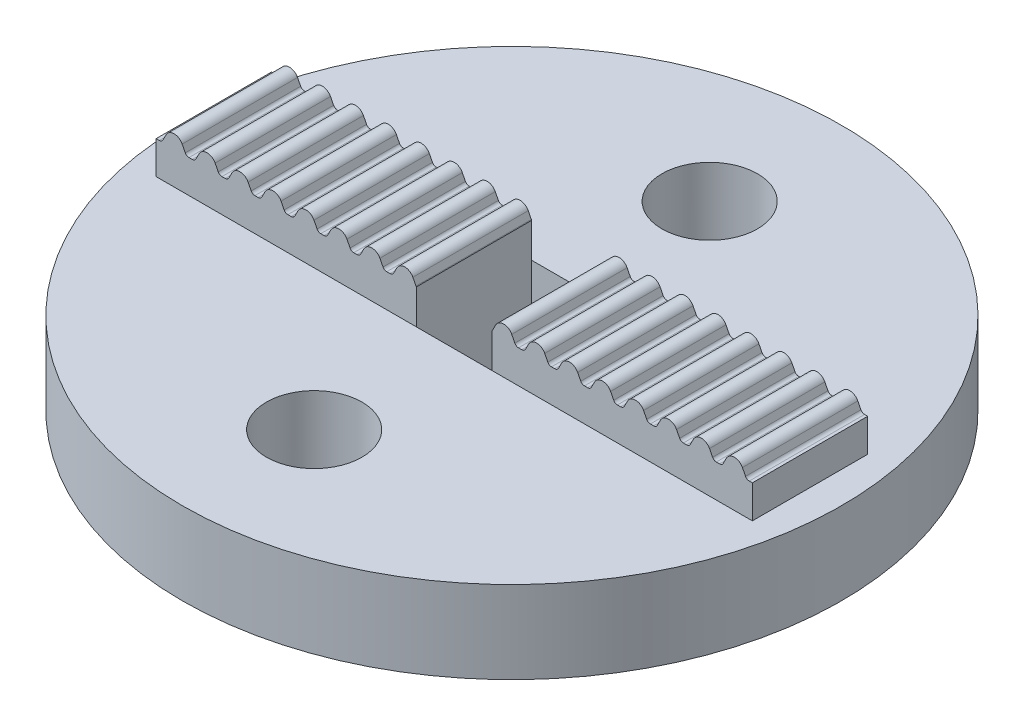
SolidWorks part; units mm, degrees
ref_plane "Front Plane" through (0, 0, 0) normal (0, 0, 1) x (1, 0, 0)
ref_plane "Top Plane" through (0, 0, 0) normal (0, 1, 0) x (1, 0, 0)
ref_plane "Right Plane" through (0, 0, 0) normal (1, 0, 0) x (0, 0, -1)
sketch "Sketch1" plane through (0, 0, 0) normal (0, 0, 1) x (1, 0, 0)
  line L0 (1.09, 0.25) -> (1.99, 0.25) construction
  line L1 (3.5789, 0.502) -> (3.7678, 0.1355)
  line L2 (3.99, 0) -> (4.18, 0)
  line L3 (1.5789, 0.502) -> (1.7678, 0.1355)
  line L4 (1.99, 0) -> (2.18, 0)
  line L5 (0.4122, 0.1355) -> (0.6011, 0.502)
  line L6 (1.09, 0.25) -> (0.19, 0.25) construction
  line L7 (0.19, 0) -> (0, 0)
  line L8 (2.4122, 0.1355) -> (2.6011, 0.502)
  line L9 (2.19, 0) -> (2, 0)
  line L10 (5.5789, 0.502) -> (5.7678, 0.1355)
  line L11 (5.99, 0) -> (6.18, 0)
  line L12 (4.4122, 0.1355) -> (4.6011, 0.502)
  line L13 (4.19, 0) -> (4, 0)
  line L14 (7.5789, 0.502) -> (7.7678, 0.1355)
  line L15 (7.99, 0) -> (8.18, 0)
  line L16 (6.4122, 0.1355) -> (6.6011, 0.502)
  line L17 (6.19, 0) -> (6, 0)
  line L18 (9.5789, 0.502) -> (9.7678, 0.1355)
  line L19 (9.99, 0) -> (10.18, 0)
  line L20 (8.4122, 0.1355) -> (8.6011, 0.502)
  line L21 (8.19, 0) -> (8, 0)
  line L22 (11.5789, 0.502) -> (11.7678, 0.1355)
  line L23 (11.99, 0) -> (12.18, 0)
  line L24 (10.4122, 0.1355) -> (10.6011, 0.502)
  line L25 (10.19, 0) -> (10, 0)
  line L26 (13.5789, 0.502) -> (13.7678, 0.1355)
  line L27 (13.99, 0) -> (14.18, 0)
  line L28 (12.4122, 0.1355) -> (12.6011, 0.502)
  line L29 (12.19, 0) -> (12, 0)
  line L30 (1.5789, 0.502) -> (3.5789, 0.502) construction
  line L31 (0, 0) -> (0, -5)
  line L32 (0, -5) -> (36.18, -5)
  line L33 (36.18, -5) -> (36.18, 0)
  line L34 (14.18, 0) -> (0, 0) construction
  line L35 (15.5789, 0.502) -> (15.7678, 0.1355)
  line L36 (15.99, 0) -> (16.18, 0)
  line L37 (14.4122, 0.1355) -> (14.6011, 0.502)
  line L38 (14.19, 0) -> (14, 0)
  line L39 (17.5789, 0.502) -> (17.7678, 0.1355)
  line L40 (17.99, 0) -> (18.18, 0)
  line L41 (16.4122, 0.1355) -> (16.6011, 0.502)
  line L42 (16.19, 0) -> (16, 0)
  line L43 (19.5789, 0.502) -> (19.7678, 0.1355)
  line L44 (19.99, 0) -> (20.18, 0)
  line L45 (18.4122, 0.1355) -> (18.6011, 0.502)
  line L46 (18.19, 0) -> (18, 0)
  line L47 (21.5789, 0.502) -> (21.7678, 0.1355)
  line L48 (21.99, 0) -> (22.18, 0)
  line L49 (20.4122, 0.1355) -> (20.6011, 0.502)
  line L50 (20.19, 0) -> (20, 0)
  line L51 (23.5789, 0.502) -> (23.7678, 0.1355)
  line L52 (23.99, 0) -> (24.18, 0)
  line L53 (22.4122, 0.1355) -> (22.6011, 0.502)
  line L54 (22.19, 0) -> (22, 0)
  line L55 (25.5789, 0.502) -> (25.7678, 0.1355)
  line L56 (25.99, 0) -> (26.18, 0)
  line L57 (24.4122, 0.1355) -> (24.6011, 0.502)
  line L58 (24.19, 0) -> (24, 0)
  line L59 (27.5789, 0.502) -> (27.7678, 0.1355)
  line L60 (27.99, 0) -> (28.18, 0)
  line L61 (26.4122, 0.1355) -> (26.6011, 0.502)
  line L62 (26.19, 0) -> (26, 0)
  line L63 (29.5789, 0.502) -> (29.7678, 0.1355)
  line L64 (29.99, 0) -> (30.18, 0)
  line L65 (28.4122, 0.1355) -> (28.6011, 0.502)
  line L66 (28.19, 0) -> (28, 0)
  line L67 (31.5789, 0.502) -> (31.7678, 0.1355)
  line L68 (31.99, 0) -> (32.18, 0)
  line L69 (30.4122, 0.1355) -> (30.6011, 0.502)
  line L70 (30.19, 0) -> (30, 0)
  line L71 (33.5789, 0.502) -> (33.7678, 0.1355)
  line L72 (33.99, 0) -> (34.18, 0)
  line L73 (32.4122, 0.1355) -> (32.6011, 0.502)
  line L74 (32.19, 0) -> (32, 0)
  line L75 (35.5789, 0.502) -> (35.7678, 0.1355)
  line L76 (35.99, 0) -> (36.18, 0)
  line L77 (34.4122, 0.1355) -> (34.6011, 0.502)
  line L78 (34.19, 0) -> (34, 0)
  arc A0 (1.5789, 0.502) -> (0.6011, 0.502) centre (1.09, 0.25) ccw
  arc A1 (1.7678, 0.1355) -> (1.99, 0) centre (1.99, 0.25) ccw
  arc A2 (0.19, 0) -> (0.4122, 0.1355) centre (0.19, 0.25) ccw
  arc A3 (3.5789, 0.502) -> (2.6011, 0.502) centre (3.09, 0.25) ccw
  arc A4 (3.7678, 0.1355) -> (3.99, 0) centre (3.99, 0.25) ccw
  arc A5 (2.19, 0) -> (2.4122, 0.1355) centre (2.19, 0.25) ccw
  arc A6 (5.5789, 0.502) -> (4.6011, 0.502) centre (5.09, 0.25) ccw
  arc A7 (5.7678, 0.1355) -> (5.99, 0) centre (5.99, 0.25) ccw
  arc A8 (4.19, 0) -> (4.4122, 0.1355) centre (4.19, 0.25) ccw
  arc A9 (7.5789, 0.502) -> (6.6011, 0.502) centre (7.09, 0.25) ccw
  arc A10 (7.7678, 0.1355) -> (7.99, 0) centre (7.99, 0.25) ccw
  arc A11 (6.19, 0) -> (6.4122, 0.1355) centre (6.19, 0.25) ccw
  arc A12 (9.5789, 0.502) -> (8.6011, 0.502) centre (9.09, 0.25) ccw
  arc A13 (9.7678, 0.1355) -> (9.99, 0) centre (9.99, 0.25) ccw
  arc A14 (8.19, 0) -> (8.4122, 0.1355) centre (8.19, 0.25) ccw
  arc A15 (11.5789, 0.502) -> (10.6011, 0.502) centre (11.09, 0.25) ccw
  arc A16 (11.7678, 0.1355) -> (11.99, 0) centre (11.99, 0.25) ccw
  arc A17 (10.19, 0) -> (10.4122, 0.1355) centre (10.19, 0.25) ccw
  arc A18 (13.5789, 0.502) -> (12.6011, 0.502) centre (13.09, 0.25) ccw
  arc A19 (13.7678, 0.1355) -> (13.99, 0) centre (13.99, 0.25) ccw
  arc A20 (12.19, 0) -> (12.4122, 0.1355) centre (12.19, 0.25) ccw
  arc A21 (15.5789, 0.502) -> (14.6011, 0.502) centre (15.09, 0.25) ccw
  arc A22 (15.7678, 0.1355) -> (15.99, 0) centre (15.99, 0.25) ccw
  arc A23 (14.19, 0) -> (14.4122, 0.1355) centre (14.19, 0.25) ccw
  arc A24 (17.5789, 0.502) -> (16.6011, 0.502) centre (17.09, 0.25) ccw
  arc A25 (17.7678, 0.1355) -> (17.99, 0) centre (17.99, 0.25) ccw
  arc A26 (16.19, 0) -> (16.4122, 0.1355) centre (16.19, 0.25) ccw
  arc A27 (19.5789, 0.502) -> (18.6011, 0.502) centre (19.09, 0.25) ccw
  arc A28 (19.7678, 0.1355) -> (19.99, 0) centre (19.99, 0.25) ccw
  arc A29 (18.19, 0) -> (18.4122, 0.1355) centre (18.19, 0.25) ccw
  arc A30 (21.5789, 0.502) -> (20.6011, 0.502) centre (21.09, 0.25) ccw
  arc A31 (21.7678, 0.1355) -> (21.99, 0) centre (21.99, 0.25) ccw
  arc A32 (20.19, 0) -> (20.4122, 0.1355) centre (20.19, 0.25) ccw
  arc A33 (23.5789, 0.502) -> (22.6011, 0.502) centre (23.09, 0.25) ccw
  arc A34 (23.7678, 0.1355) -> (23.99, 0) centre (23.99, 0.25) ccw
  arc A35 (22.19, 0) -> (22.4122, 0.1355) centre (22.19, 0.25) ccw
  arc A36 (25.5789, 0.502) -> (24.6011, 0.502) centre (25.09, 0.25) ccw
  arc A37 (25.7678, 0.1355) -> (25.99, 0) centre (25.99, 0.25) ccw
  arc A38 (24.19, 0) -> (24.4122, 0.1355) centre (24.19, 0.25) ccw
  arc A39 (27.5789, 0.502) -> (26.6011, 0.502) centre (27.09, 0.25) ccw
  arc A40 (27.7678, 0.1355) -> (27.99, 0) centre (27.99, 0.25) ccw
  arc A41 (26.19, 0) -> (26.4122, 0.1355) centre (26.19, 0.25) ccw
  arc A42 (29.5789, 0.502) -> (28.6011, 0.502) centre (29.09, 0.25) ccw
  arc A43 (29.7678, 0.1355) -> (29.99, 0) centre (29.99, 0.25) ccw
  arc A44 (28.19, 0) -> (28.4122, 0.1355) centre (28.19, 0.25) ccw
  arc A45 (31.5789, 0.502) -> (30.6011, 0.502) centre (31.09, 0.25) ccw
  arc A46 (31.7678, 0.1355) -> (31.99, 0) centre (31.99, 0.25) ccw
  arc A47 (30.19, 0) -> (30.4122, 0.1355) centre (30.19, 0.25) ccw
  arc A48 (33.5789, 0.502) -> (32.6011, 0.502) centre (33.09, 0.25) ccw
  arc A49 (33.7678, 0.1355) -> (33.99, 0) centre (33.99, 0.25) ccw
  arc A50 (32.19, 0) -> (32.4122, 0.1355) centre (32.19, 0.25) ccw
  arc A51 (35.5789, 0.502) -> (34.6011, 0.502) centre (35.09, 0.25) ccw
  arc A52 (35.7678, 0.1355) -> (35.99, 0) centre (35.99, 0.25) ccw
  arc A53 (34.19, 0) -> (34.4122, 0.1355) centre (34.19, 0.25) ccw
  point P203 (36.3294, 0)
  dimension "D1" = 1.1
  dimension "D2" = 0.5
  dimension "D3" = 0.9
  dimension "D4" = 0.19
  dimension "D5" = 0.19
  dimension "D7" = 2
  dimension "D8" = 5
  dimension "D9" = 36.18
  dimension "D6" = 18
extrude "Boss-Extrude1" add sketch "Sketch1" along normal blind 7 contours A20 L29 L23 A16 L22 A15 L24 A17 L25 L19 A13 L18 A12 L20 A14 L21 L15 A10 L14 A9 L16 A11 L17 L11 A7 L10 A6 L12 A8 L13 L2 A4 L1 A3 L8 A5 L9 L4 A1 L3 A0 L5 A2 L7 L31
sketch "Sketch2" plane through (0, 0, 0) normal (0, 1, 0) x (1, 0, 0)
  line L0 (0, -7) -> (36.18, 0) construction
  circle A0 centre (18.09, -3.5) radius 20
  dimension "D1" = 40
extrude "Boss-Extrude2" add sketch "Sketch2" against normal blind 5 from offset 2 offset against normal yes
sketch "Sketch4" plane through (0, -2, 0) normal (0, 1, 0) x (1, 0, 0)
  line L0 (0, 0) -> (36.18, 0)
  line L3 (15.79, 0) -> (20.39, 0)
  line L4 (15.79, 0) -> (15.79, -7)
  line L5 (15.79, -7) -> (20.39, -7)
  line L6 (20.39, 0) -> (20.39, -7)
  point P4 (18.09, 0)
  point P6 (0, 0)
  point P7 (20.09, -10.4186)
  point P12 (0, 0)
  line M6 (36.18, -7) -> (0, -7)
  dimension "D1" = 7
  dimension "D2" = 4.6
extrude "Cut-Extrude2" cut sketch "Sketch4" against normal through all both and the other way through all contours L6 L0 L4 M6
sketch "Sketch5" plane through (0, -7, 0) normal (0, -1, 0) x (1, 0, 0)
  line L0 (18.09, 3.5) -> (18.09, 15.5) construction
  line L3 (18.09, 3.5) -> (18.09, -8.5) construction
  dimension "D1" = 12
hole_wizard "M5 Clearance Hole1" positions "3DSketch1" profile "Sketch6" hole size "M5" standard "ANSI Metric" end condition through all
sketch3d "3DSketch1"
  point P0 (18.09, -7, 15.5)
  point P3 (18.09, -7, -8.5)
sketch "Sketch6" plane through (18.09, -7, 15.5) normal (1, 0, 0) x (0, 0, -1)
  line L0 (0, 0) -> (0, 7.8)
  line L1 (0, 7.8) -> (2.9, 7.8)
  line L2 (2.9, 7.8) -> (2.9, 0)
  line L5 (2.9, 0) -> (0, 0)
  line L11 (0, -6.35) -> (0, 107.95) construction
  dimension "Thru Hole Dia." = 5.8
  dimension "Thru Hole Depth" = 7.8
